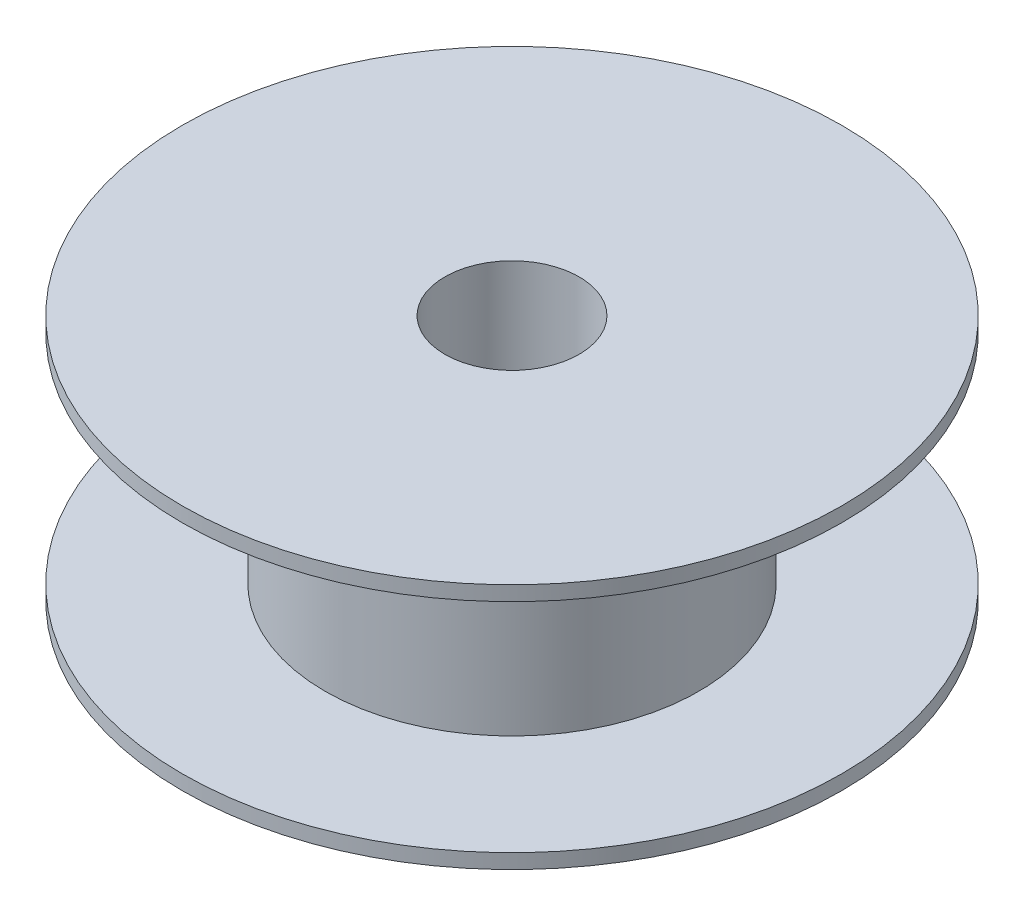
SolidWorks part; units mm, degrees
ref_plane "Front Plane" through (0, 0, 0) normal (0, 0, 1) x (1, 0, 0)
ref_plane "Top Plane" through (0, 0, 0) normal (0, 1, 0) x (1, 0, 0)
ref_plane "Right Plane" through (0, 0, 0) normal (1, 0, 0) x (0, 0, -1)
sketch "Sketch1" plane through (0, 0, 0) normal (0, 0, 1) x (1, 0, 0)
  line L0 (0, 0) -> (0, 101)
  line L2 (0, 0) -> (-135, 0)
  line L3 (0, 0) -> (0, 6)
  line L4 (-76.5, 6) -> (-135, 6)
  line L5 (-135, 0) -> (-135, 6)
  line L7 (0, 6) -> (0, 95)
  line L9 (-76.5, 6) -> (-76.5, 95)
  line L10 (-76.5, 95) -> (-135, 95)
  line L11 (0, 95) -> (0, 101)
  line L12 (0, 101) -> (-135, 101)
  line L13 (-135, 95) -> (-135, 101)
  dimension "D1" = 101
  dimension "D2" = 6
  dimension "D3" = 135
  dimension "D4" = 89
  dimension "D5" = 76.5
  dimension "D6" = 6
  dimension "D7" = 6
  dimension "D8" = 135
revolve "Revolve1" add sketch "Sketch1" angle 360 about L0
sketch "Sketch2" plane through (0, 101, 0) normal (0, 1, 0) x (1, 0, 0)
  line L0 (0, 135) -> (0, -135) construction
  circle A0 centre (0, 0) radius 135 construction
  circle A1 centre (0, 0) radius 27.5
  dimension "D1" = 55
extrude "Cut-Extrude1" cut sketch "Sketch2" against normal blind 260
